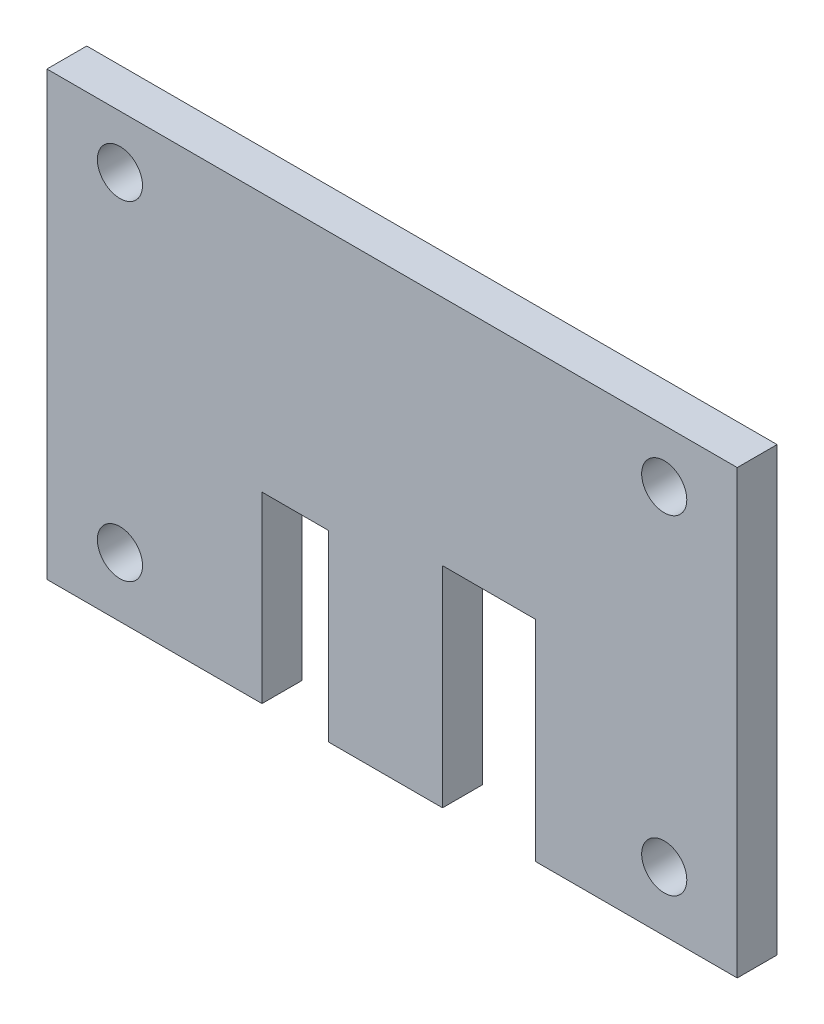
SolidWorks part; units mm, degrees
ref_plane "Front Plane" through (0, 0, 0) normal (0, 0, 1) x (1, 0, 0)
ref_plane "Top Plane" through (0, 0, 0) normal (0, 1, 0) x (1, 0, 0)
ref_plane "Right Plane" through (0, 0, 0) normal (1, 0, 0) x (0, 0, -1)
ref_plane "PY124_4" through (0, 0, 124.4) normal (0, 0, 1) x (1, 0, 0)
sketch "Sketch1" plane through (0, 0, 124.4) normal (0, 0, 1) x (1, 0, 0)
  line L0 (-62.5, -26.8) -> (-10.5, -26.8)
  line L1 (-10.5, -26.8) -> (-10.5, 6.5)
  line L2 (-10.5, 6.5) -> (-62.5, 6.5)
  line L3 (-62.5, 6.5) -> (-62.5, -26.8)
extrude "Cover Plate" add sketch "Sketch1" along normal blind 3
ref_plane "PY123_4" through (0, 0, 123.4) normal (0, 0, 1) x (1, 0, 0)
sketch "Sketch2" plane through (0, 0, 123.4) normal (0, 0, 1) x (1, 0, 0)
  line L0 (-46.3, -27.8) -> (-41.3, -27.8)
  line L1 (-41.3, -27.8) -> (-41.3, -13)
  line L2 (-41.3, -13) -> (-46.3, -13)
  line L3 (-46.3, -13) -> (-46.3, -27.8)
  line L4 (-32.7, -27.8) -> (-25.7, -27.8)
  line L5 (-25.7, -27.8) -> (-25.7, -11)
  line L6 (-25.7, -11) -> (-32.7, -11)
  line L7 (-32.7, -11) -> (-32.7, -27.8)
extrude "Cable Notches" cut sketch "Sketch2" along normal blind 5
sketch "Sketch3" plane through (0, 0, 123.4) normal (0, 0, 1) x (1, 0, 0)
  circle A0 centre (-57, -22.3) radius 1.7
  circle A1 centre (-57, 2.5) radius 1.7
  circle A2 centre (-16, -22.3) radius 1.7
  circle A3 centre (-16, 2.5) radius 1.7
extrude "Screw Holes" cut sketch "Sketch3" along normal blind 5
equation "\"BOARD_REAR\" = 86.0"
equation "\"BOARD_FRONT\" = 41.0"
equation "\"BOARD_END\" = 22.0"
equation "\"BOARD_ANGLED\" = 30.0"
equation "\"BOARD_DEPTH\" = 41.8431"
equation "\"PCB_T\" = 1.6"
equation "\"ABOVE_PCB\" = 14.0"
equation "\"BELOW_PCB\" = 6.0"
equation "\"MID_PARTS_H\" = 9.0"
equation "\"BOARD_HOLE_PILOT\" = 1.6"
equation "\"J2_X\" = 19.0"
equation "\"DUPONT_DROP\" = 14.0"
equation "\"BEND_R\" = 5.0"
equation "\"BOARD_GAP\" = 3.0"
equation "\"TOF_FOV\" = 25.0"
equation "\"TOF_MARGIN_DEG\" = 5.0"
equation "\"TOF_WIN_MARGIN\" = 1.0"
equation "\"TOF_Z\" = 9.0"
equation "\"TOF_SIDE_BEARING\" = 90.0"
equation "\"TOF_CONE_LEN\" = 70.0"
equation "\"CAM_W\" = 29.2"
equation "\"CAM_H\" = 28.2"
equation "\"CAM_D\" = 12.35"
equation "\"CAM_FRONT_Y\" = 43.0"
equation "\"CAM_BOTTOM_Z\" = 17.0"
equation "\"CAM_LENS_UP\" = 11.6"
equation "\"CAM_LENS_OPEN\" = 9.6"
equation "\"CAM_HFOV\" = 53.5"
equation "\"CAM_VFOV\" = 41.41"
equation "\"CAM_FOV_MARGIN\" = 3.0"
equation "\"CAM_FIT\" = 0.3"
equation "\"RIBBON_W\" = 16.0"
equation "\"RIBBON_T\" = 0.3"
equation "\"RIBBON_LEN\" = 150.0"
equation "\"RIBBON_EXIT_Y\" = 35.0"
equation "\"WALL\" = 2.4"
equation "\"HEAD_X\" = 48.4"
equation "\"HEAD_REAR_Y\" = -11.9"
equation "\"CAM_FOAM\" = 2.8"
equation "\"HEAD_FRONT_Y\" = 48.2"
equation "\"HEAD_TOP_Z\" = 50.6"
equation "\"HEAD_BOT_Z\" = -28.4"
equation "\"HEAD_SPLIT_Z\" = -4.0"
equation "\"SKIRT_T\" = 1.2"
equation "\"SKIRT_H\" = 3.0"
equation "\"SKIRT_FIT\" = 0.3"
equation "\"VISOR\" = 7.8"
equation "\"VISOR_Z\" = 40.0"
equation "\"ROOF_SLOPE_Y\" = 40.0"
equation "\"ROOF_CHAMFER\" = 10.0"
equation "\"REAR_CHAMFER\" = 10.0"
equation "\"CORNER_CHAMFER\" = 6.0"
equation "\"LOWER_SIDE_FACET\" = 6.0"
equation "\"LIGHTBAR_DEPTH\" = 1.0"
equation "\"HOOD_Z\" = 14.0"
equation "\"HOOD_L\" = 6.0"
equation "\"SIDE_HOOD_L\" = 4.0"
equation "\"INSERT_M3_D\" = 4.0"
equation "\"INSERT_M3_L\" = 6.0"
equation "\"M3_CLEAR\" = 3.4"
equation "\"M2_PILOT\" = 1.6"
equation "\"M25_PILOT\" = 2.2"
equation "\"BOX_X\" = 72.4"
equation "\"BOX_FRONT_Y\" = -11.9"
equation "\"BOX_REAR_Y\" = -124.4"
equation "\"BOX_BOT_Z\" = -28.4"
equation "\"BOX_TOP_Z\" = 26.0"
equation "\"LID_T\" = 2.4"
equation "\"LID_SKIRT\" = 1.6"
equation "\"LID_TONGUE_H\" = 3.0"
equation "\"LID_FIT\" = 0.3"
equation "\"PI_STANDOFF\" = 8.0"
equation "\"BOX_REAR_CHAMFER\" = 8.0"
equation "\"BOX_REAR_FACET\" = 4.0"
equation "\"VENT_UPSTAND\" = 3.0"
equation "\"TUBE_D\" = 22.2"
equation "\"TUBE_LINER\" = 1.0"
equation "\"MOUNT_Y\" = -70.0"
equation "\"RAIL_W\" = 30.0"
equation "\"RAIL_W2\" = 38.0"
equation "\"RAIL_H\" = 6.0"
equation "\"SLIDE\" = 0.3"
equation "\"STOP_T\" = 6.0"
equation "\"CLAMP_W\" = 40.0"
equation "\"CLAMP_HALF\" = 20.0"
equation "\"CLAMP_DROP\" = 12.0"
equation "\"CAP_T\" = 12.0"
equation "\"CLAMP_BOLT_OFF\" = 16.6"
equation "\"M5_INSERT_D\" = 6.4"
equation "\"M5_CLEAR\" = 5.5"
equation "\"LOCK_D\" = 3.3"
equation "\"POD_TILT_DEG\" = 0.0"
equation "\"PRINT_LIMIT\" = 180.0"
equation "\"PI5_L\" = 85.0"
equation "\"PI5_W\" = 56.0"
equation "\"PI5_T\" = 1.6"
equation "\"PI5_USBC_BX\" = 11.2"
equation "\"PI5_ETH_BY\" = 10.2"
equation "\"PI5_PORT_OVERHANG\" = 3.0"
equation "\"PI5_FPC_H\" = 5.0"
equation "\"PI5_FPC_USE\" = 0.0"
equation "\"PI5_PIN1_BX\" = 8.37"
equation "\"HEADER_BASE_H\" = 2.5"
equation "\"DUPONT_L\" = 14.0"
equation "\"PI5_UNDERSIDE\" = 1.5"
equation "\"COOLER_H\" = 15.0"
equation "\"HAT_W\" = 65.0"
equation "\"HAT_D\" = 56.5"
equation "\"HAT_T\" = 1.6"
equation "\"HAT_SPACER\" = 16.0"
equation "\"HAILO_H\" = 10.0"
equation "\"STACK_PINS_H\" = 6.0"
equation "\"DUPONT_SEAT\" = 0.5"
equation "\"PCIE_FFC_LOOP\" = 6.0"
equation "\"HAILO_AIR_GAP_MIN\" = 8.0"
equation "\"M25_CLEAR\" = 2.7"
equation "\"PI_X0\" = -55.0"
equation "\"PI_Y1\" = -36.5"
equation "\"PI_Y0\" = -92.5"
equation "\"BOX_LEN\" = 112.5"
equation "\"COVER_T\" = 3.0"
equation "\"COVER_TOP_Z\" = 6.5"
equation "\"SIDE_LEDGE_Z\" = -2.5"
equation "\"UPPER_LEDGE_Z\" = 15.5"
equation "\"REAR_LEDGE_Z\" = 8.0"
equation "\"LEDGE_L\" = 4.0"
equation "\"RIBBON_W_PI\" = 11.5"
equation "\"RIBBON_RUN_Z\" = 12.0"
equation "\"RIBBON_SPEC_LEN\" = 200.0"
